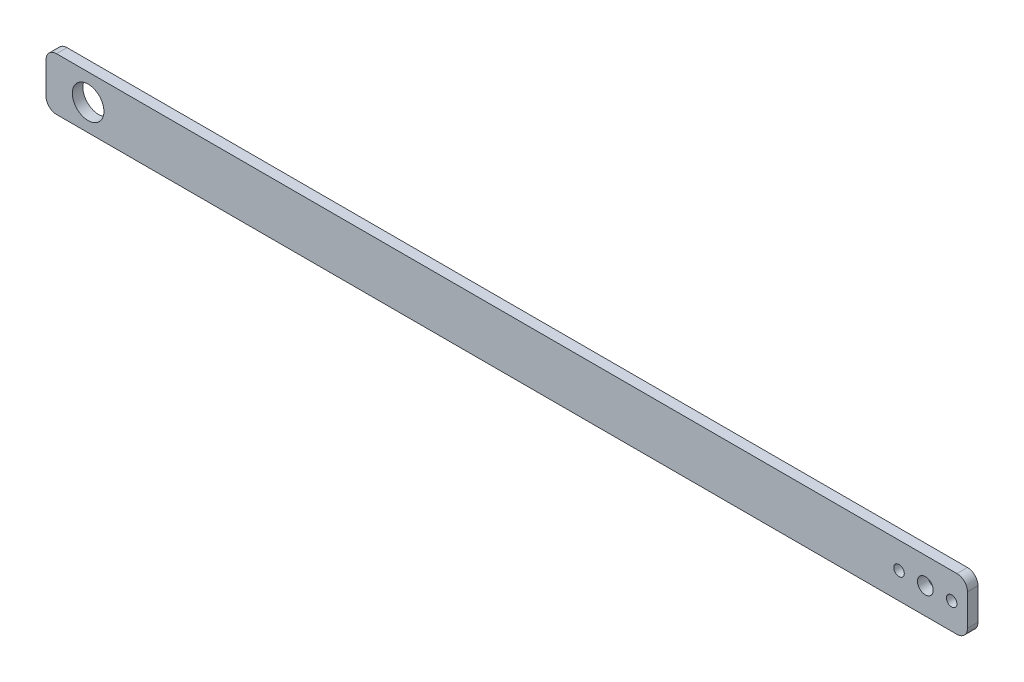
SolidWorks part; units mm, degrees
ref_plane "前视基准面" through (0, 0, 0) normal (0, 0, 1) x (1, 0, 0)
ref_plane "上视基准面" through (0, 0, 0) normal (0, 1, 0) x (1, 0, 0)
ref_plane "右视基准面" through (0, 0, 0) normal (1, 0, 0) x (0, 0, -1)
sketch "草图1" plane through (0, 0, 0) normal (0, 0, 1) x (1, 0, 0)
  line L1 (-170, 0) -> (5, 0)
  line L2 (-170, 0) -> (-170, -10)
  line L3 (-170, -10) -> (5, -10)
  line L4 (5, 0) -> (5, -10)
  point P4 (-170, -5)
  dimension "D1" = 175
  dimension "D2" = 10
extrude "凸台-拉伸1" add sketch "草图1" along normal blind 2
sketch "草图2" plane through (0, 0, 2) normal (0, 0, 1) x (1, 0, 0)
  line L0 (-170, -5) -> (-162, -5)
  line L1 (-170, 0) -> (-170, -10) construction
  circle A0 centre (-162, -5) radius 3
  dimension "D2" = 6
  dimension "D1" = 8
extrude "切除-拉伸1" cut sketch "草图2" against normal blind 15 and the other way blind 12
ref_plane "基准面1" through (-82.5, 0, 0) normal (-1, 0, 0) x (0, 0, 1)
sketch "草图3" plane through (0, 0, 2) normal (0, 0, 1) x (1, 0, 0)
  line L0 (5, -10) -> (5, 0) construction
  circle A0 centre (-3, -5) radius 1.5
  circle A1 centre (-8, -5) radius 1
  circle A2 centre (2, -5) radius 1
  dimension "D1" = 5
  dimension "D4" = 3
  dimension "D2" = 5
  dimension "D3" = 3
extrude "切除-拉伸2" cut sketch "草图3" against normal blind 10
fillet "圆角1" radius 2 4 edges at (-170, -10, 1) (-170, 0, 1) (5, 0, 1) (5, -10, 1)
